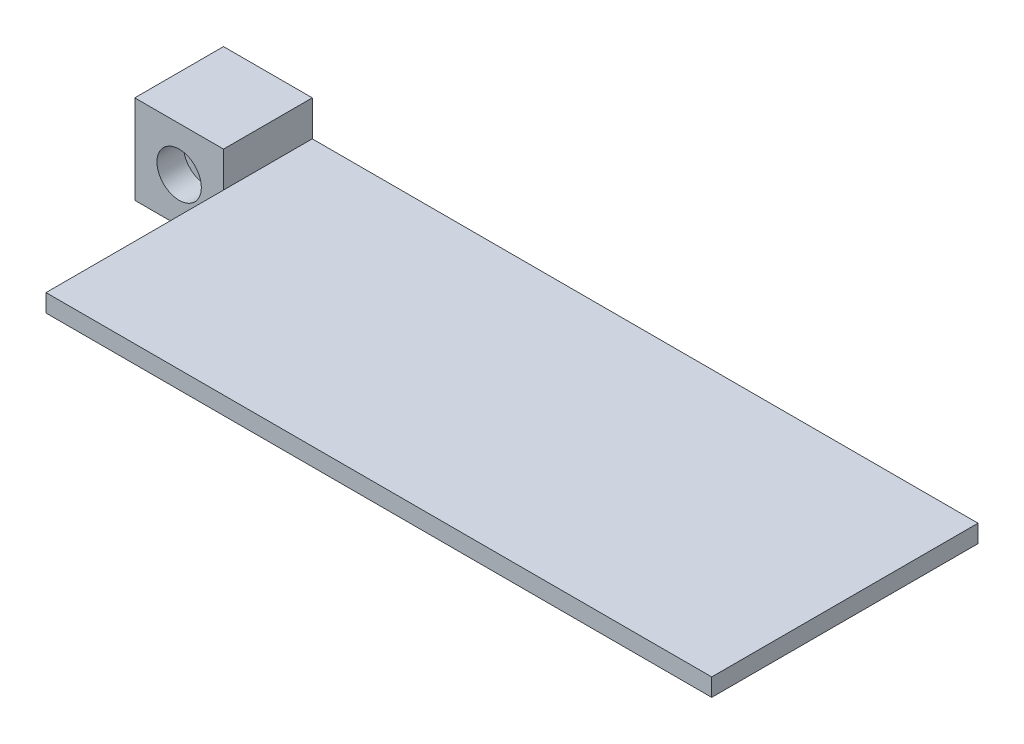
SolidWorks part; units mm, degrees
ref_plane "Front Plane" through (0, 0, 0) normal (0, 0, 1) x (1, 0, 0)
ref_plane "Top Plane" through (0, 0, 0) normal (0, 1, 0) x (1, 0, 0)
ref_plane "Right Plane" through (0, 0, 0) normal (1, 0, 0) x (0, 0, -1)
sketch "Sketch1" plane through (0, 0, 0) normal (0, 0, 1) x (1, 0, 0)
  line L1 (-42.5, 15) -> (42.5, 15)
  line L2 (-42.5, 15) -> (-42.5, -15)
  line L3 (-42.5, -15) -> (42.5, -15)
  line L4 (42.5, 15) -> (42.5, -15)
  line L5 (-42.5, 15) -> (42.5, -15) construction
  line L6 (-42.5, -15) -> (42.5, 15) construction
  point P0 (0, 0)
  dimension "D1" = 30
  dimension "D2" = 85
extrude "Boss-Extrude1" add sketch "Sketch1" along normal blind 30
sketch "Sketch2" plane through (0, 0, 30) normal (0, 0, 1) x (1, 0, 0)
  line L0 (-42.5, 0) -> (-32.5, 0)
  line L1 (-42.5, 15) -> (-42.5, -15) construction
  line L2 (-32.5, 0) -> (-32.5, -4)
  line L3 (-32.5, -4) -> (42.5, -4)
  line L4 (42.5, -15) -> (42.5, 15) construction
  line L5 (42.5, -4) -> (42.5, 15)
  line L6 (42.5, 15) -> (-42.5, 15)
  line L7 (-42.5, 15) -> (-42.5, 0)
  line L8 (-42.5, -10) -> (-32.5, -10)
  line L9 (-32.5, -10) -> (-32.5, -6)
  line L10 (-32.5, -6) -> (42.5, -6)
  line L11 (42.5, -6) -> (42.5, -15)
  line L12 (42.5, -15) -> (-42.5, -15)
  line L13 (-42.5, -15) -> (-42.5, -10)
  dimension "D1" = 10
  dimension "D2" = 4
  dimension "D3" = 10
  dimension "D4" = 4
  dimension "D5" = 10
extrude "Cut-Extrude1" cut sketch "Sketch2" against normal blind 30
sketch "Sketch3" plane through (0, 0, 30) normal (0, 0, 1) x (1, 0, 0)
  line L1 (-42.5, 0) -> (-32.5, 0)
  line L2 (-42.5, 0) -> (-42.5, -10)
  line L3 (-42.5, -10) -> (-32.5, -10)
  line L4 (-32.5, 0) -> (-32.5, -10)
extrude "Cut-Extrude2" cut sketch "Sketch3" against normal blind 20
sketch "Sketch4" plane through (0, 0, 0) normal (0, 0, -1) x (-1, 0, 0)
  line L0 (42.5, 0) -> (42.5, -10) construction
  line L1 (42.5, 0) -> (32.5, 0) construction
  circle A0 centre (37.5, -5) radius 2.5
  point P6 (37.5, 0)
  dimension "D1" = 5
  dimension "D2" = 5
  dimension "D3" = 5
extrude "Cut-Extrude3" cut sketch "Sketch4" against normal blind 4
sketch "Sketch5" plane through (0, 0, 10) normal (0, 0, 1) x (1, 0, 0)
  line L0 (-42.5, 0) -> (-42.5, -10) construction
  line L1 (-42.5, -10) -> (-32.5, -10) construction
  circle A0 centre (-37.5, -5) radius 2.5
  dimension "D1" = 5
  dimension "D2" = 5
  dimension "D3" = 5
extrude "Cut-Extrude4" cut sketch "Sketch5" against normal blind 3
sketch "Sketch6" plane through (0, 0, 7) normal (0, 0, 1) x (1, 0, 0)
  line L0 (-42.5, 0) -> (-42.5, -10) construction
  line L1 (-42.5, -10) -> (-32.5, -10) construction
  circle A0 centre (-37.5, -5) radius 1
  dimension "D1" = 2
  dimension "D3" = 5
  dimension "D2" = 5
extrude "Cut-Extrude5" cut sketch "Sketch6" against normal through all
